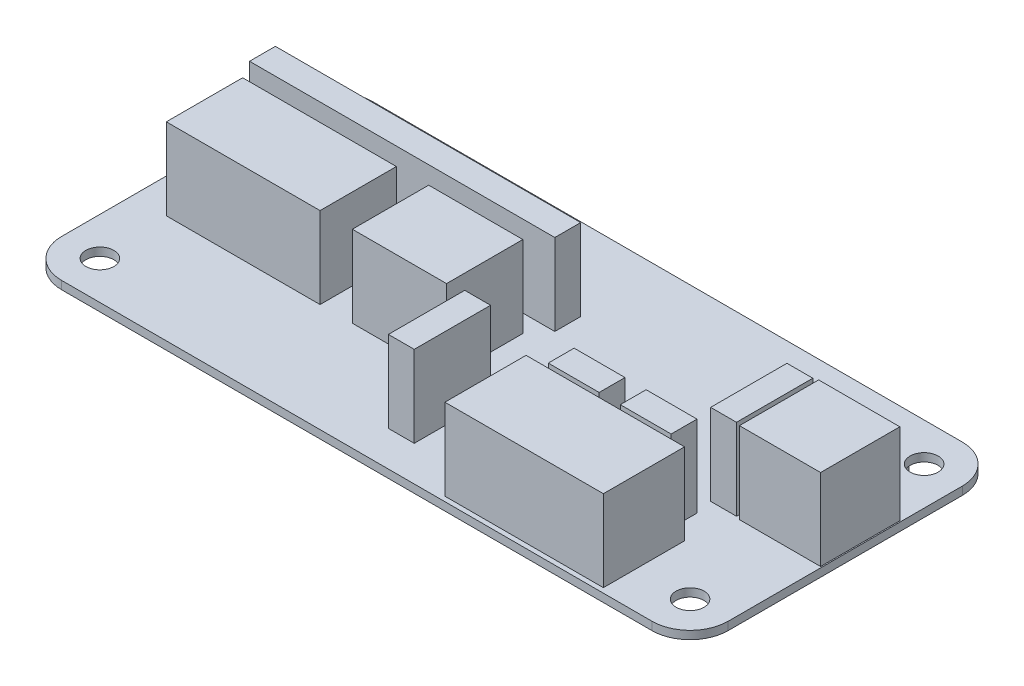
SolidWorks part; units mm, degrees
ref_plane "Front Plane" through (0, 0, 0) normal (0, 0, 1) x (1, 0, 0)
ref_plane "Top Plane" through (0, 0, 0) normal (0, 1, 0) x (1, 0, 0)
ref_plane "Right Plane" through (0, 0, 0) normal (1, 0, 0) x (0, 0, -1)
sketch "Sketch1" plane through (0, 0, 0) normal (0, 1, 0) x (1, 0, 0)
  line L0 (-32.75, 15.25) -> (32.75, 15.25)
  line L1 (-32.75, 15.25) -> (-32.75, -15.25)
  line L2 (32.75, 15.25) -> (32.75, -15.25)
  line L3 (-32.75, -15.25) -> (32.75, -15.25)
  line L4 (-32.75, 15.25) -> (32.75, -15.25) construction
  line L5 (32.75, 15.25) -> (-32.75, -15.25) construction
  point P1 (0, 0)
  dimension "D1" = 30.5
  dimension "D2" = 65.5
extrude "Boss-Extrude1" add sketch "Sketch1" along normal blind 0.8
fillet "Fillet1" radius 3.75 4 edges at (-32.75, 0.4, -15.25) (-32.75, 0.4, 15.25) (32.75, 0.4, -15.25) (32.75, 0.4, 15.25)
sketch "Sketch2" plane through (0, 0.8, 0) normal (0, 1, 0) x (1, 0, 0)
  circle A0 centre (-29, 11.5) radius 1.375
  circle A1 centre (-29, -11.5) radius 1.375
  circle A2 centre (29, -11.5) radius 1.375
  circle A3 centre (29, 11.5) radius 1.375
  dimension "D1" = 2.75
extrude "Cut-Extrude1" cut sketch "Sketch2" against normal blind 0.8
sketch "Sketch3" plane through (0, 0.8, 0) normal (0, 1, 0) x (1, 0, 0)
  line L0 (-30.4263, 7.1728) -> (-0.4263, 7.1728)
  line L1 (-30.4263, 7.1728) -> (-30.4263, 4.6328)
  line L2 (-0.4263, 7.1728) -> (-0.4263, 4.6328)
  line L3 (-30.4263, 4.6328) -> (-0.4263, 4.6328)
  line L4 (-30.4263, 7.1728) -> (-0.4263, 4.6328) construction
  line L5 (-0.4263, 7.1728) -> (-30.4263, 4.6328) construction
  line L6 (-11.0788, 2.8908) -> (-1.8256, 2.8908)
  line L7 (-11.0788, 2.8908) -> (-11.0788, -4.6092)
  line L8 (-1.8256, 2.8908) -> (-1.8256, -4.6092)
  line L9 (-11.0788, -4.6092) -> (-1.8256, -4.6092)
  line L10 (-11.0788, 2.8908) -> (-1.8256, -4.6092) construction
  line L11 (-1.8256, 2.8908) -> (-11.0788, -4.6092) construction
  line L12 (-29.3612, 2.8908) -> (-29.3612, -4.6092)
  line L13 (-29.3612, 2.8908) -> (-14.2526, 2.8908)
  line L14 (-29.3612, -4.6092) -> (-14.2526, -4.6092)
  line L15 (-14.2526, 2.8908) -> (-14.2526, -4.6092)
  line L16 (-29.3612, 2.8908) -> (-14.2526, -4.6092) construction
  line L17 (-29.3612, -4.6092) -> (-14.2526, 2.8908) construction
  line L18 (-0.3559, -4.2903) -> (-0.3559, -11.7903)
  line L19 (-0.3559, -4.2903) -> (2.1841, -4.2903)
  line L20 (-0.3559, -11.7903) -> (2.1841, -11.7903)
  line L21 (2.1841, -4.2903) -> (2.1841, -11.7903)
  line L22 (-0.3559, -4.2903) -> (2.1841, -11.7903) construction
  line L23 (-0.3559, -11.7903) -> (2.1841, -4.2903) construction
  line L24 (8.1894, -6.8064) -> (23.7626, -6.8064)
  line L25 (8.1894, -6.8064) -> (8.1894, -14.7824)
  line L26 (23.7626, -6.8064) -> (23.7626, -14.7824)
  line L27 (8.1894, -14.7824) -> (23.7626, -14.7824)
  line L28 (8.1894, -6.8064) -> (23.7626, -14.7824) construction
  line L29 (23.7626, -6.8064) -> (8.1894, -14.7824) construction
  line L30 (24.2251, 5.3354) -> (24.2251, -2.1646)
  line L31 (24.2251, 5.3354) -> (21.6851, 5.3354)
  line L32 (24.2251, -2.1646) -> (21.6851, -2.1646)
  line L33 (21.6851, 5.3354) -> (21.6851, -2.1646)
  line L34 (24.2251, 5.3354) -> (21.6851, -2.1646) construction
  line L35 (24.2251, -2.1646) -> (21.6851, 5.3354) construction
  line L36 (9.938, -3.8345) -> (14.938, -3.8345)
  line L37 (9.938, -3.8345) -> (9.938, -6.3745)
  line L38 (14.938, -3.8345) -> (14.938, -6.3745)
  line L39 (9.938, -6.3745) -> (14.938, -6.3745)
  line L40 (9.938, -3.8345) -> (14.938, -6.3745) construction
  line L41 (14.938, -3.8345) -> (9.938, -6.3745) construction
  line L42 (17.014, -3.8345) -> (17.014, -6.3745)
  line L43 (17.014, -3.8345) -> (22.014, -3.8345)
  line L44 (17.014, -6.3745) -> (22.014, -6.3745)
  line L45 (22.014, -3.8345) -> (22.014, -6.3745)
  line L46 (17.014, -3.8345) -> (22.014, -6.3745) construction
  line L47 (17.014, -6.3745) -> (22.014, -3.8345) construction
  line L48 (24.657, 5.4786) -> (24.657, -2.3079)
  line L49 (24.657, 5.4786) -> (32.633, 5.4786)
  line L50 (24.657, -2.3079) -> (32.633, -2.3079)
  line L51 (32.633, 5.4786) -> (32.633, -2.3079)
  line L52 (24.657, 5.4786) -> (32.633, -2.3079) construction
  line L53 (24.657, -2.3079) -> (32.633, 5.4786) construction
  line L54 (15.976, -10.7944) -> (23.7626, -10.7944) construction
  line L55 (28.645, 1.5854) -> (22.9551, 1.5854) construction
  line L56 (12.438, -5.1045) -> (19.514, -5.1045) construction
  line L57 (15.976, -10.7944) -> (15.976, -5.1045) construction
  point P1 (-15.4263, 5.9028)
  point P2 (-6.4522, -0.8592)
  point P3 (-21.8069, -0.8592)
  point P4 (0.9141, -8.0403)
  point P5 (15.976, -10.7944)
  point P6 (22.9551, 1.5854)
  point P7 (12.438, -5.1045)
  point P8 (19.514, -5.1045)
  point P13 (28.645, 1.5854)
  dimension "D1" = 2.54
  dimension "D2" = 7.5
  dimension "D3" = 5
  dimension "D4" = 30
extrude "Boss-Extrude2" add sketch "Sketch3" along normal blind 8
sketch "Sketch4" plane through (0, 0, 0) normal (0, -1, 0) x (1, 0, 0)
  line L0 (25.25, -8.8) -> (-25.75, -8.8)
  line L1 (25.25, -8.8) -> (25.25, -13.75)
  line L2 (-25.75, -8.8) -> (-25.75, -13.75)
  line L3 (25.25, -13.75) -> (-25.75, -13.75)
  line L4 (25.25, -8.8) -> (-25.75, -13.75) construction
  line L5 (-25.75, -8.8) -> (25.25, -13.75) construction
  line L6 (29, -15.25) -> (-29, -15.25) construction
  line L7 (-32.75, -11.5) -> (-32.75, 11.5) construction
  point P1 (-0.25, -11.275)
  dimension "D1" = 51
  dimension "D2" = 4.95
  dimension "D3" = 1.5
  dimension "D4" = 7
extrude "Boss-Extrude3" add sketch "Sketch4" along normal blind 4
